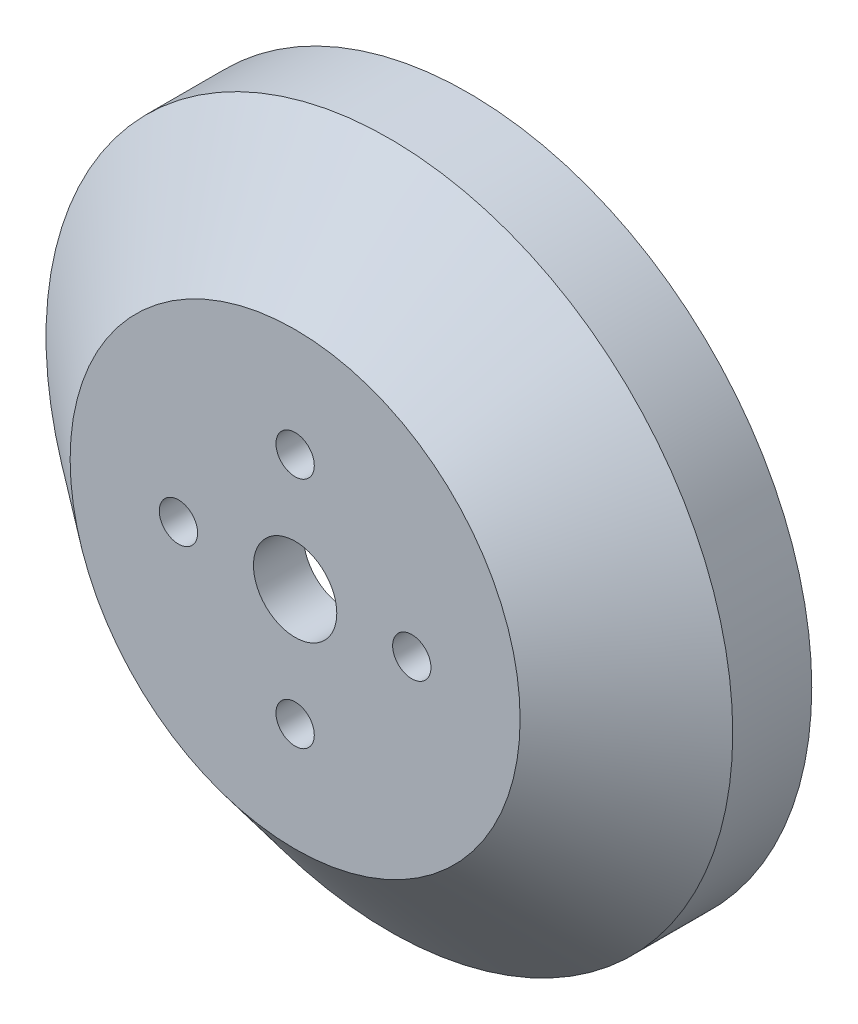
SolidWorks part; units mm, degrees
ref_plane "前视基准面" through (0, 0, 0) normal (0, 0, 1) x (1, 0, 0)
ref_plane "上视基准面" through (0, 0, 0) normal (0, 1, 0) x (1, 0, 0)
ref_plane "右视基准面" through (0, 0, 0) normal (1, 0, 0) x (0, 0, -1)
other "Configuration Table"
sketch "草图1" plane through (0, 0, 0) normal (0, 0, 1) x (1, 0, 0)
  circle A0 centre (0, 0) radius 13.5
  circle A1 centre (0, 0) radius 7 construction
  circle A2 centre (0, 7) radius 1.15
  circle A3 centre (0, -7) radius 1.15
  circle A4 centre (7, 0) radius 1.15
  circle A5 centre (-7, 0) radius 1.15
  circle A6 centre (0, 0) radius 2.5
  dimension "D1" = 27
  dimension "D2" = 14
  dimension "D3" = 2.3
  dimension "D4" = 5
extrude "凸台-拉伸1" add sketch "草图1" along normal blind 3
sketch "草图2" plane through (0, 0, 0) normal (1, 0, 0) x (0, 0, -1)
  line L0 (-3, 13.5) -> (2.6562, 20.6013)
  line L2 (4.779, 19.5) -> (0, 13.5)
  line L3 (0, -13.5) -> (0, 13.5) construction
  line L4 (0, 0) -> (27.8481, 0) construction
  line L5 (0, 13.5) -> (-3, 13.5)
  line L7 (2.6562, 20.6013) -> (7.3972, 20.6013)
  line L9 (4.779, 19.5) -> (7.3972, 19.5)
  line L10 (7.3972, 20.6013) -> (7.3972, 19.5)
  point P4 (4.779, 19.5)
  dimension "D1" = 6
  dimension "D2" = 7.3972
revolve "旋转1" add sketch "草图2" angle 360 about L4
